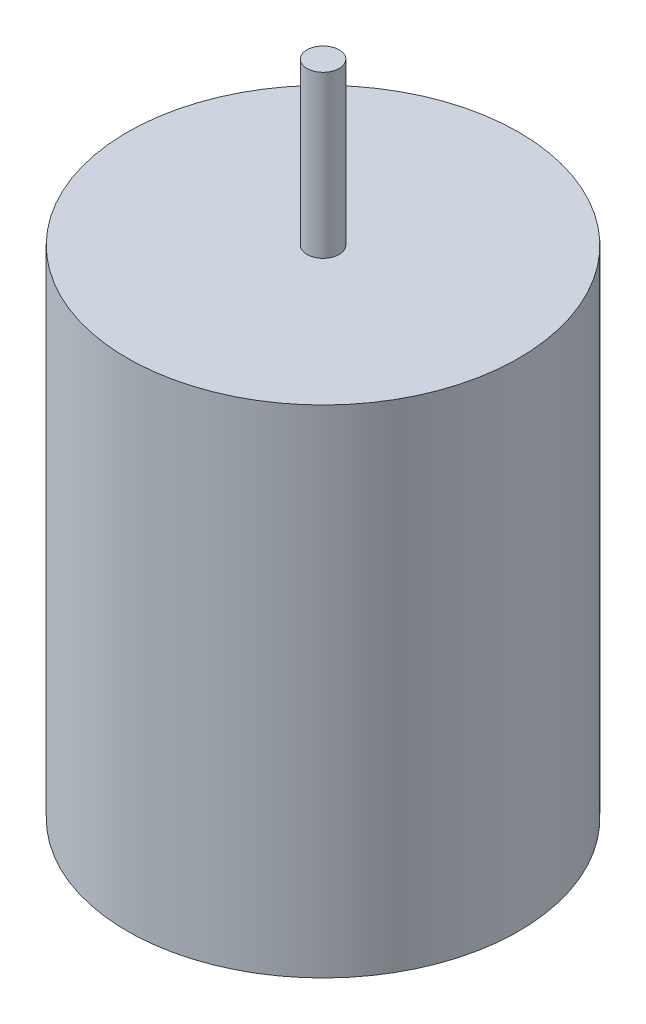
SolidWorks part; units mm, degrees
ref_plane "Front Plane" through (0, 0, 0) normal (0, 0, 1) x (1, 0, 0)
ref_plane "Top Plane" through (0, 0, 0) normal (0, 1, 0) x (1, 0, 0)
ref_plane "Right Plane" through (0, 0, 0) normal (1, 0, 0) x (0, 0, -1)
sketch "Sketch1" plane through (0, 0, 0) normal (0, 1, 0) x (1, 0, 0)
  circle A0 centre (0, 0) radius 12.15
  dimension "D1" = 24.3
extrude "Boss-Extrude1" add sketch "Sketch1" along normal blind 30.8
sketch "Sketch2" plane through (0, 30.8, 0) normal (0, 1, 0) x (1, 0, 0)
  circle A0 centre (0, 0) radius 1
  dimension "D1" = 2
extrude "Boss-Extrude2" add sketch "Sketch2" along normal blind 10
